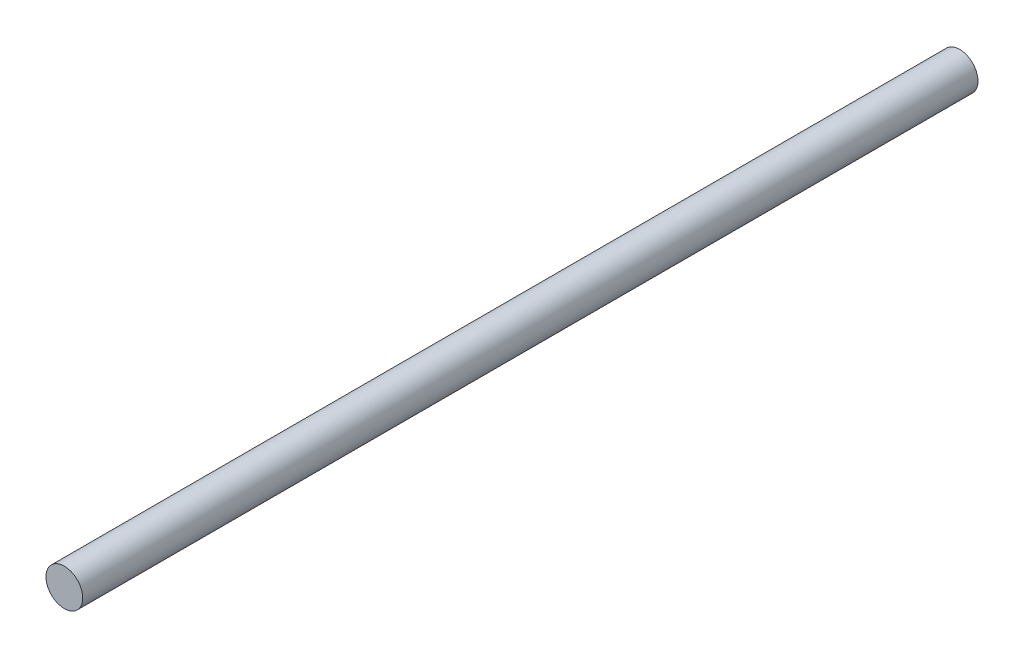
SolidWorks part; units mm, degrees
ref_plane "Plano frontal" through (0, 0, 0) normal (0, 0, 1) x (1, 0, 0)
ref_plane "Plano superior" through (0, 0, 0) normal (0, 1, 0) x (1, 0, 0)
ref_plane "Plano direito" through (0, 0, 0) normal (1, 0, 0) x (0, 0, -1)
sketch "Esboço1" plane through (0, 0, 0) normal (0, 0, 1) x (1, 0, 0)
  circle A0 centre (0, 0) radius 1.5
  dimension "D1" = 3
extrude "Ressalto-extrusão1" add sketch "Esboço1" along normal blind 73
